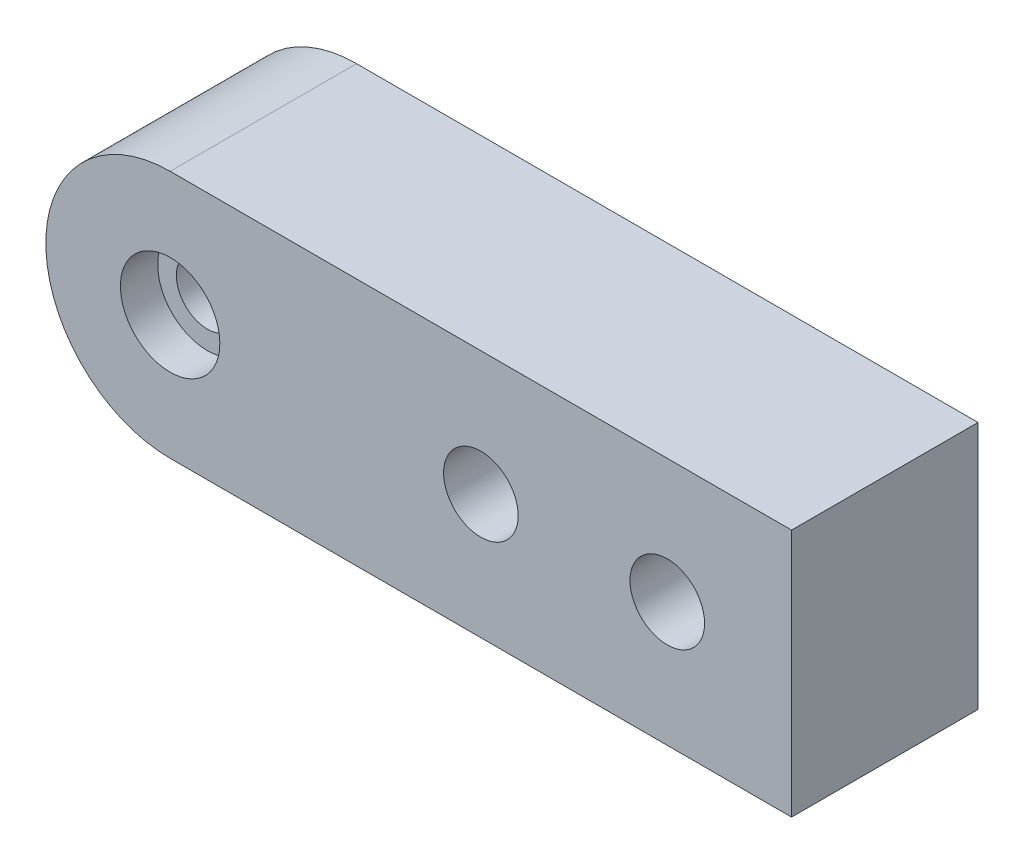
SolidWorks part; units mm, degrees
ref_plane "前视基准面" through (0, 0, 0) normal (0, 0, 1) x (1, 0, 0)
ref_plane "上视基准面" through (0, 0, 0) normal (0, 1, 0) x (1, 0, 0)
ref_plane "右视基准面" through (0, 0, 0) normal (1, 0, 0) x (0, 0, -1)
other "Configuration Table"
sketch "草图1" plane through (0, 0, 0) normal (0, 0, 1) x (1, 0, 0)
  line L0 (-50, 0) -> (0, 0)
  line L1 (0, 0) -> (0, -20)
  line L2 (0, -20) -> (-50, -20)
  line L3 (0, -10) -> (-50000, -10) construction
  arc A0 (-50, 0) -> (-50, -20) centre (-50, -10) ccw
  circle A1 centre (-25, -10) radius 3
  circle A2 centre (-10, -10) radius 3
  point P17 (0, -10)
  dimension "D1" = 6
  dimension "D2" = 6
  dimension "D3" = 15
  dimension "D4" = 10
  dimension "D5" = 25
  dimension "D6" = 20
extrude "凸台-拉伸1" add sketch "草图1" along normal blind 15
sketch "草图2" plane through (0, 0, 15) normal (0, 0, 1) x (1, 0, 0)
  circle A0 centre (-50, -10) radius 4
  dimension "D1" = 8
extrude "切除-拉伸1" cut sketch "草图2" against normal blind 3
sketch "草图3" plane through (0, 0, 12) normal (0, 0, 1) x (1, 0, 0)
  circle A0 centre (-50, -10) radius 2.5
  dimension "D1" = 5
extrude "切除-拉伸2" cut sketch "草图3" against normal blind 15
sketch "草图4" plane through (0, 0, 0) normal (0, 0, -1) x (-1, 0, 0)
  circle A0 centre (10, -10) radius 5
  circle A1 centre (25, -10) radius 5
  dimension "D1" = 10
  dimension "D2" = 10
extrude "切除-拉伸3" cut sketch "草图4" against normal blind 6
